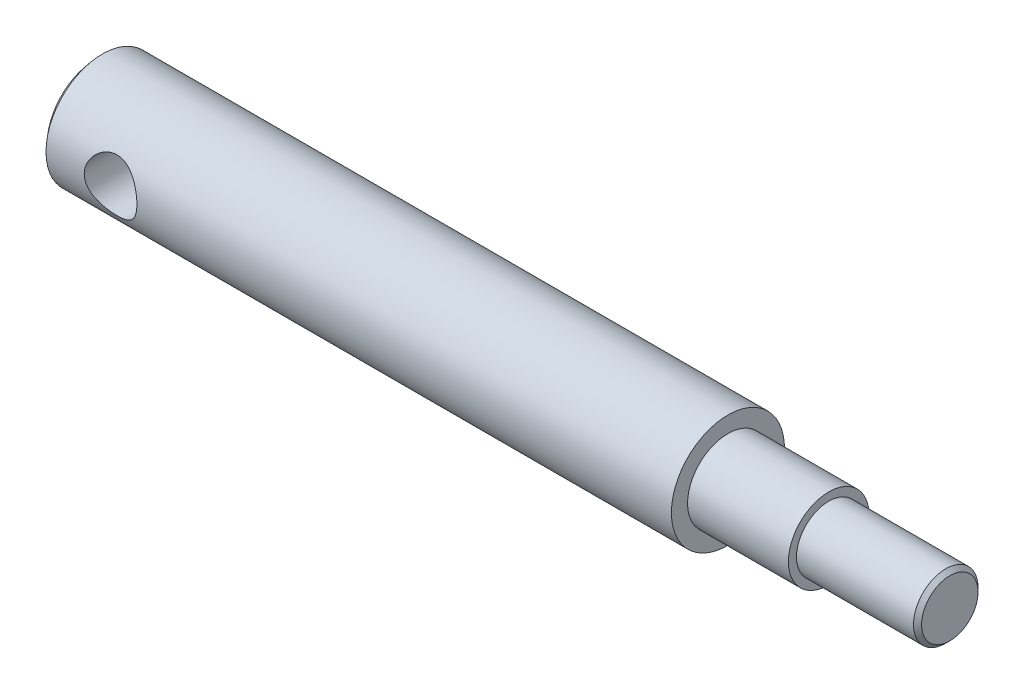
SolidWorks part; units mm, degrees
ref_plane "Płaszczyzna przednia" through (0, 0, 0) normal (0, 0, 1) x (1, 0, 0)
ref_plane "Płaszczyzna górna" through (0, 0, 0) normal (0, 1, 0) x (1, 0, 0)
ref_plane "Płaszczyzna prawa" through (0, 0, 0) normal (1, 0, 0) x (0, 0, -1)
sketch "Sketch1" plane through (0, 0, 0) normal (0, 0, 1) x (1, 0, 0)
  line L2 (186, 10) -> (161, 10)
  line L3 (161, 10) -> (161, 14)
  line L4 (161, 14) -> (6, 14)
  line L5 (0, 0) -> (216, 0)
  line L6 (216, 0) -> (216, 7)
  line L7 (215, 8) -> (186, 8)
  line L8 (186, 8) -> (186, 10)
  line L9 (216, 7) -> (215, 8)
  arc A0 (6, 14) -> (0, 0) centre (21.9709, -1.1304) ccw
  point P9 (216, 8)
  dimension "D8" = 22
  dimension "D1" = 155
  dimension "D2" = 6
  dimension "D3" = 25
  dimension "D4" = 30
  dimension "D5" = 8
  dimension "D6" = 10
  dimension "D7" = 14
revolve "Revolve1" add sketch "Sketch1" angle 360 about L5
cosmetic thread "Cosmetic Thread1"
sketch "Sketch2" plane through (0, 0, 0) normal (0, 0, 1) x (1, 0, 0)
  circle A0 centre (22, 0) radius 6.525
  dimension "D1" = 13.05
  dimension "D2" = 22
extrude "Cut-Extrude1" cut sketch "Sketch2" against normal mid plane 40
